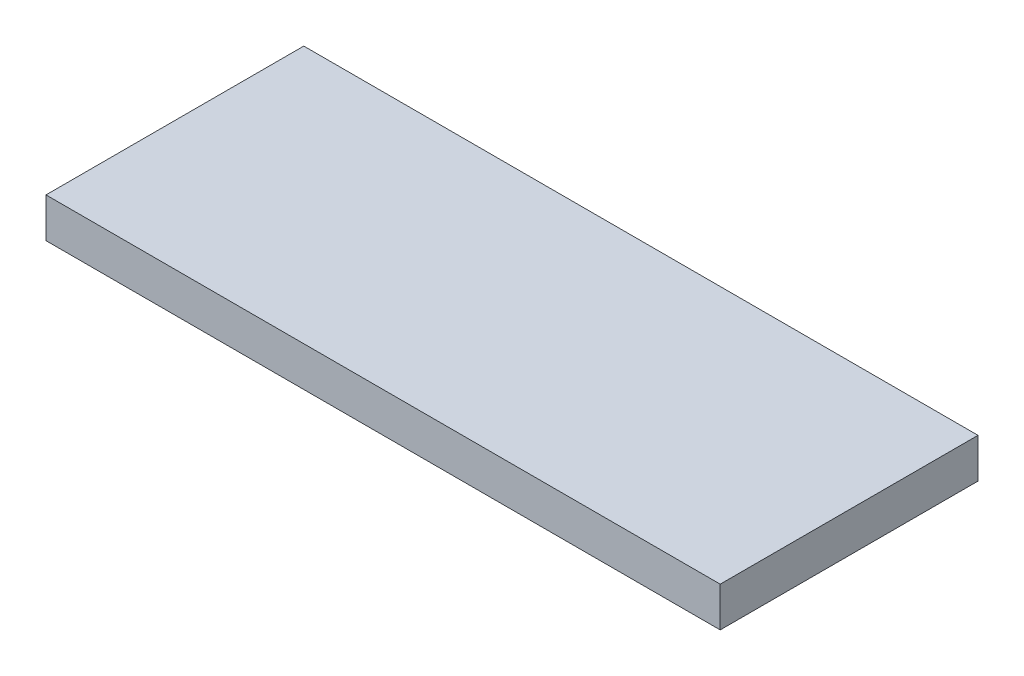
SolidWorks part; units mm, degrees
ref_plane "Front Plane" through (0, 0, 0) normal (0, 0, 1) x (1, 0, 0)
ref_plane "Top Plane" through (0, 0, 0) normal (0, 1, 0) x (1, 0, 0)
ref_plane "Right Plane" through (0, 0, 0) normal (1, 0, 0) x (0, 0, -1)
sketch "Sketch1" plane through (0, 0, 0) normal (0, 1, 0) x (1, 0, 0)
  line L1 (-85, 32.5) -> (85, 32.5)
  line L2 (-85, 32.5) -> (-85, -32.5)
  line L3 (-85, -32.5) -> (85, -32.5)
  line L4 (85, 32.5) -> (85, -32.5)
  line L5 (-85, 32.5) -> (85, -32.5) construction
  line L6 (-85, -32.5) -> (85, 32.5) construction
  point P0 (0, 0)
  dimension "D1" = 170
  dimension "D2" = 65
extrude "Boss-Extrude1" add sketch "Sketch1" along normal blind 10
sketch "Sketch2" plane through (0, 0, -32.5) normal (0, 0, -1) x (-1, 0, 0)
  line L0 (85, 10) -> (85, 0) construction
  line L1 (73.149, 2.5763) -> (62.2917, 2.5763)
  line L2 (73.149, 2.5763) -> (73.149, 5.8887)
  line L3 (73.149, 5.8887) -> (62.2917, 5.8887)
  line L4 (62.2917, 2.5763) -> (62.2917, 5.8887)
  line L5 (57.5071, 2.5763) -> (44.9935, 2.5763)
  line L6 (57.5071, 2.5763) -> (57.5071, 5.8887)
  line L7 (57.5071, 5.8887) -> (44.9935, 5.8887)
  line L8 (44.9935, 2.5763) -> (44.9935, 5.8887)
  line L9 (30.8238, 2.5763) -> (17.5742, 2.5763)
  line L10 (30.8238, 2.5763) -> (30.8238, 7.913)
  line L11 (30.8238, 7.913) -> (17.5742, 7.913)
  line L12 (17.5742, 2.5763) -> (17.5742, 7.913)
  line L13 (9.1091, 2.5763) -> (-5.2446, 2.5763)
  line L14 (9.1091, 2.5763) -> (9.1091, 7.913)
  line L15 (9.1091, 7.913) -> (-5.2446, 7.913)
  line L16 (-5.2446, 2.5763) -> (-5.2446, 7.913)
  line L17 (-14.8138, 2.5763) -> (-29.1676, 2.5763)
  line L18 (-14.8138, 2.5763) -> (-14.8138, 7.913)
  line L19 (-14.8138, 7.913) -> (-29.1676, 7.913)
  line L20 (-29.1676, 2.5763) -> (-29.1676, 7.913)
  line L21 (-43.7054, 2.5763) -> (-70.5727, 2.5763)
  line L22 (-43.7054, 2.5763) -> (-43.7054, 5.2446)
  line L23 (-43.7054, 5.2446) -> (-70.5727, 5.2446)
  line L24 (-70.5727, 2.5763) -> (-70.5727, 5.2446)
  line L25 (-85, 0) -> (85, 0) construction
  dimension "D1" = 11.851
  dimension "D2" = 22.7083
  dimension "D3" = 27.4929
  dimension "D4" = 40.0065
  dimension "D5" = 54.1762
  dimension "D6" = 67.4258
  dimension "D7" = 75.8909
  dimension "D8" = 90.2446
  dimension "D9" = 99.8138
  dimension "D10" = 114.1676
  dimension "D11" = 128.7054
  dimension "D12" = 155.5727
  dimension "D13" = 2.5763
  dimension "D14" = 2.5763
  dimension "D15" = 5.2446
  dimension "D16" = 5.8887
  dimension "D17" = 5.8887
  dimension "D18" = 7.913
  dimension "D19" = 7.913
extrude "Cut-Extrude1" cut sketch "Sketch2" against normal blind 5
